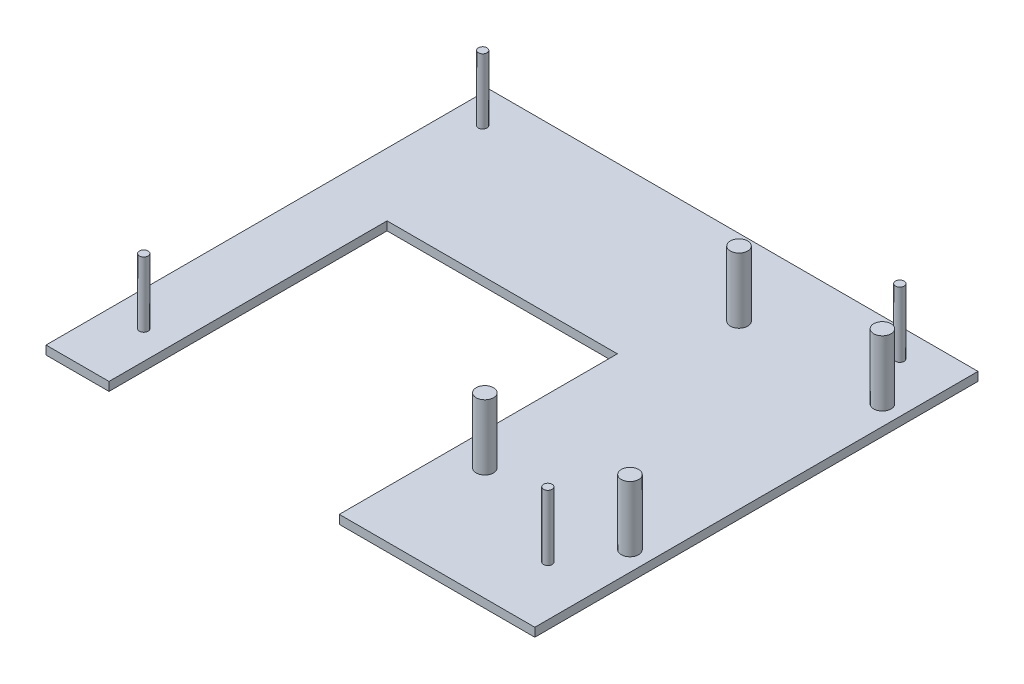
SolidWorks part; units mm, degrees
ref_plane "정면" through (0, 0, 0) normal (0, 0, 1) x (1, 0, 0)
ref_plane "윗면" through (0, 0, 0) normal (0, 1, 0) x (1, 0, 0)
ref_plane "우측면" through (0, 0, 0) normal (1, 0, 0) x (0, 0, -1)
sketch "스케치1" plane through (0, 0, 0) normal (0, 1, 0) x (1, 0, 0)
  line L1 (-60, 60) -> (60, 60)
  line L2 (-60, 60) -> (-60, -60)
  line L3 (-60, -60) -> (60, -60)
  line L4 (60, 60) -> (60, -60)
  line L5 (-60, 60) -> (60, -60) construction
  line L6 (-60, -60) -> (60, 60) construction
  point P0 (0, 0)
  dimension "D1" = 120
  dimension "D2" = 120
extrude "보스-돌출1" add sketch "스케치1" along normal blind 2
sketch "스케치2" plane through (0, 2, 0) normal (0, 1, 0) x (1, 0, 0)
  circle A0 centre (55.5, 24.5) radius 2
  circle A1 centre (55.5, -33.6) radius 2
  circle A2 centre (48.5, -45.5) radius 1
  circle A3 centre (22.5, -34) radius 2
  circle A4 centre (22.5, 24.5) radius 2
  circle A5 centre (48.5, 35.5) radius 1
  circle A6 centre (-46, 34) radius 1
  circle A7 centre (-44.5, -45.5) radius 1
  dimension "D1" = 4
  dimension "D2" = 4
  dimension "D3" = 2
  dimension "D4" = 4
  dimension "D5" = 4
  dimension "D6" = 2
  dimension "D7" = 2
  dimension "D8" = 2
extrude "보스-돌출2" add sketch "스케치2" along normal blind 15
sketch "스케치3" plane through (0, 2, 0) normal (0, 1, 0) x (1, 0, 0)
  line L0 (-60, -60) -> (60, -60) construction
  line L1 (60, 60) -> (15, 60)
  line L2 (60, 60) -> (60, -60)
  line L3 (60, -60) -> (15, -60)
  line L4 (15, 60) -> (15, -60)
  line L5 (-60, 60) -> (-60, -60) construction
  line L6 (-60, 29) -> (15, 29)
  line L7 (-60, 29) -> (-60, 60)
  line L8 (-60, 60) -> (15, 60)
  line L9 (15, 29) -> (15, 60)
  line L10 (-52.5, -60) -> (-52.5, 60)
  line L11 (-60, 60) -> (-38, 60)
  line L14 (-38, 60) -> (-38, -60)
  line L15 (-60, 42) -> (60, 42)
  circle A0 centre (-44.5, -45.5) radius 1 construction
  circle A1 centre (-46, 34) radius 1 construction
  circle A2 centre (22.5, 24.5) radius 2 construction
  circle A3 centre (48.5, 35.5) radius 1 construction
  line M10 (60, 60) -> (-60, 60)
  line M11 (-60, 60) -> (-60, -60)
  line M12 (-60, -60) -> (60, -60)
  dimension "D1" = 6.5
  dimension "D2" = 6.5
  dimension "D5" = 6.5
  dimension "D3" = 5
  dimension "D4" = 7.5
extrude "컷-돌출3" cut sketch "스케치3" against normal blind 15 contours L14 L15 L4 M10 | L4 L15 L2 M10 | L10 L15 L14 L8 | L15 L10 L8 M11 | L15 L7 L6 L10 | L10 L6 M12 M11
sketch "스케치4" plane through (0, 2, 0) normal (0, 1, 0) x (1, 0, 0)
  line L0 (-52.5, -60) -> (60, -60) construction
  line L1 (-38, 4) -> (15, 4)
  line L2 (-38, 4) -> (-38, -60)
  line L3 (-38, -60) -> (15, -60)
  line L4 (15, 4) -> (15, -60)
  circle A0 centre (-46, 34) radius 1 construction
  circle A1 centre (22.5, -34) radius 2 construction
  circle A2 centre (-44.5, -45.5) radius 1 construction
  dimension "D1" = 30
  dimension "D2" = 7.5
  dimension "D3" = 6.5
extrude "컷-돌출4" cut sketch "스케치4" against normal blind 15
